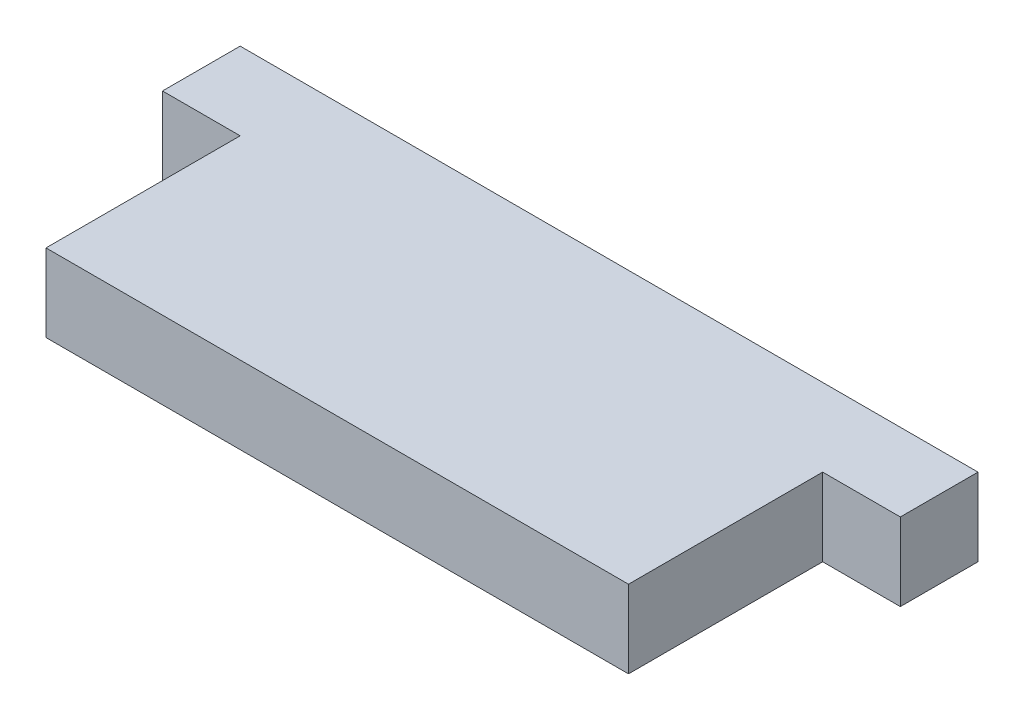
SolidWorks part; units mm, degrees
ref_plane "Front Plane" through (0, 0, 0) normal (0, 0, 1) x (1, 0, 0)
ref_plane "Top Plane" through (0, 0, 0) normal (0, 1, 0) x (1, 0, 0)
ref_plane "Right Plane" through (0, 0, 0) normal (1, 0, 0) x (0, 0, -1)
sketch "Sketch1" plane through (0, 0, 0) normal (0, 0, 1) x (1, 0, 0)
  line L1 (-7.5, 1) -> (7.5, 1)
  line L2 (-7.5, 1) -> (-7.5, -1)
  line L3 (-7.5, -1) -> (7.5, -1)
  line L4 (7.5, 1) -> (7.5, -1)
  dimension "D1" = 15
  dimension "D2" = 1
  dimension "D3" = 2
  dimension "D4" = 7.5
extrude "Boss-Extrude1" add sketch "Sketch1" along normal blind 5
sketch "Sketch2" plane through (0, 0, 0) normal (0, 0, -1) x (-1, 0, 0)
  line L0 (-7.5, 1) -> (7.5, 1) construction
  line L1 (-9.5, 1) -> (9.5, 1)
  line L2 (-9.5, 1) -> (-9.5, -1)
  line L3 (-9.5, -1) -> (9.5, -1)
  line L4 (9.5, 1) -> (9.5, -1)
  line L5 (7.5, -1) -> (-7.5, -1) construction
  line L6 (-7.5, -1) -> (-7.5, 1) construction
  line L7 (7.5, 1) -> (7.5, -1) construction
  dimension "D1" = 2
  dimension "D2" = 2
extrude "Boss-Extrude2" add sketch "Sketch2" along normal blind 2
sketch "Sketch3" plane through (0, 1, 0) normal (0, 1, 0) x (1, 0, 0)
  line L0 (7.5, -5) -> (-7.5, -5) construction
  line L1 (8.3749, -5) -> (1.6251, -5)
  arc A0 (1.6251, -5) -> (8.3749, -5) centre (5, -2.5) ccw construction
  arc A1 (1.6251, -5) -> (8.3749, -5) centre (5, -2.5) ccw
extrude "Boss-Extrude3" [suppressed] add sketch "Sketch3" against normal blind 2
sketch "Sketch4" [suppressed] plane through (0, 1, 0) normal (0, 1, 0) x (1, 0, 0)
  circle A0 centre (0, -2.5) radius 2.1
  dimension "D1" = 4.2
extrude "Cut-Extrude1" [suppressed] cut sketch "Sketch4" against normal blind 10
